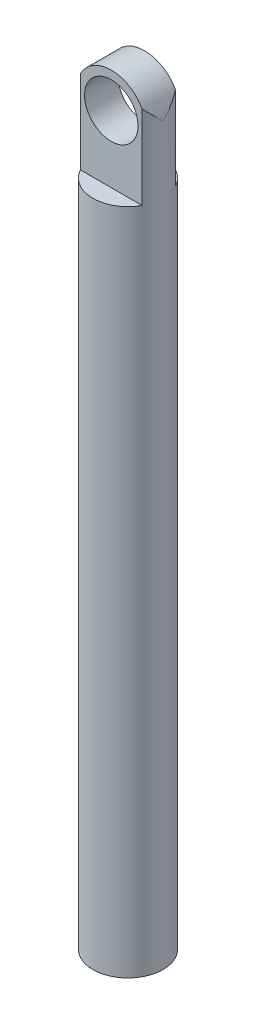
SolidWorks part; units mm, degrees
ref_plane "Front Plane" through (0, 0, 0) normal (0, 0, 1) x (1, 0, 0)
ref_plane "Top Plane" through (0, 0, 0) normal (0, 1, 0) x (1, 0, 0)
ref_plane "Right Plane" through (0, 0, 0) normal (1, 0, 0) x (0, 0, -1)
sketch "Sketch1" plane through (0, 0, 0) normal (0, 1, 0) x (1, 0, 0)
  circle A0 centre (0, 0) radius 5.25
  dimension "D1" = 10.5
extrude "Boss-Extrude1" add sketch "Sketch1" along normal blind 100
sketch "Sketch2" plane through (0, 0, 0) normal (0, 0, 1) x (1, 0, 0)
  line L0 (-5.25, 100) -> (-5.25, 110)
  line L1 (5.25, 110) -> (5.25, 100)
  line L2 (-5.25, 100) -> (5.25, 100)
  arc A0 (-5.25, 110) -> (5.25, 110) centre (0, 110) cw
  dimension "D1" = 10
extrude "Boss-Extrude2" add sketch "Sketch2" along normal mid plane 5
sketch "Sketch3" plane through (0, 100, 0) normal (0, 1, 0) x (1, 0, 0)
  circle A0 centre (0, 0) radius 5.25
  arc A1 (-4.6165, -2.5) -> (4.6165, -2.5) centre (0, 0) ccw construction
extrude "Cut-Extrude1" cut sketch "Sketch3" along normal through all flip side to cut
sketch "Sketch4" plane through (0, 0, 2.5) normal (0, 0, 1) x (1, 0, 0)
  circle A0 centre (0, 110) radius 4
  arc A1 (4.6165, 112.5) -> (-4.6165, 112.5) centre (0, 110) ccw construction
  dimension "D1" = 8
extrude "Cut-Extrude2" cut sketch "Sketch4" against normal through all
sketch "Sketch5" plane through (0, 0, 0) normal (0, -1, 0) x (1, 0, 0)
  circle A0 centre (0, 0) radius 2.65
  dimension "D1" = 5.3
extrude "Cut-Extrude3" cut sketch "Sketch5" against normal blind 6
